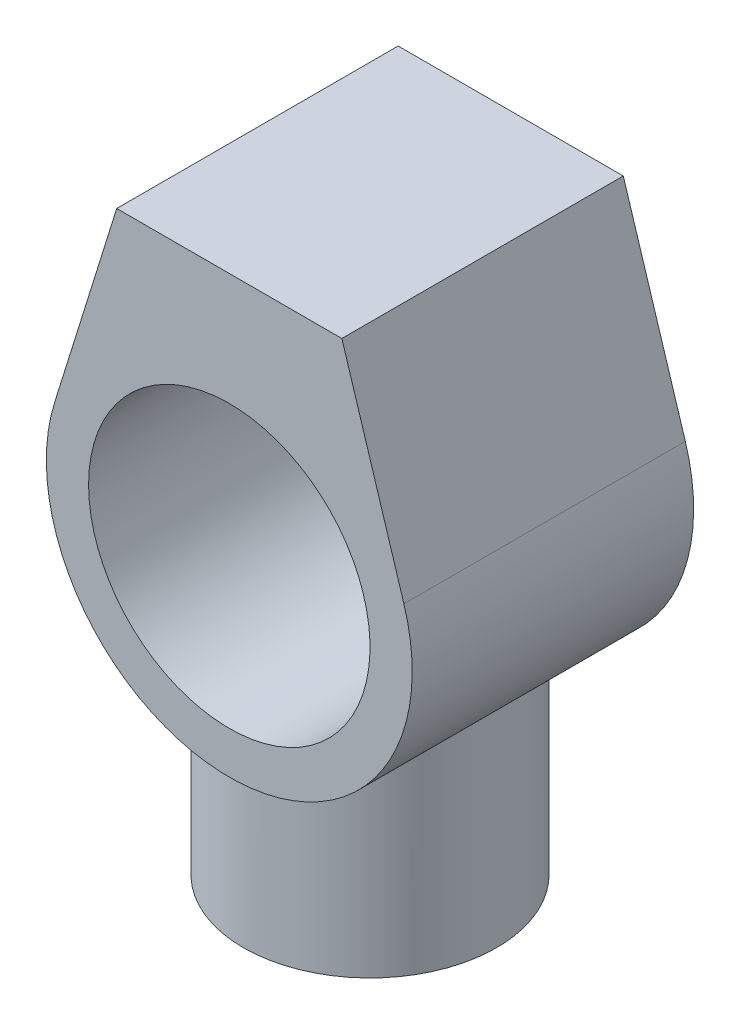
SolidWorks part; units mm, degrees
material "普通碳钢"
ref_plane "Front Plane" through (0, 0, 0) normal (0, 0, 1) x (1, 0, 0)
ref_plane "Top Plane" through (0, 0, 0) normal (0, 1, 0) x (1, 0, 0)
ref_plane "Right Plane" through (0, 0, 0) normal (1, 0, 0) x (0, 0, -1)
sketch "Sketch1" plane through (0, 0, 0) normal (0, 0, 1) x (1, 0, 0)
  line L0 (-40, 90) -> (40, 90)
  line L1 (-40, 90) -> (-62.0475, 19.3678)
  line L2 (40, 90) -> (62.0475, 19.3678)
  circle A0 centre (0, 0) radius 50
  arc A1 (-62.0475, 19.3678) -> (62.0475, 19.3678) centre (0, 0) ccw
  point P7 (0, 90)
  dimension "D1" = 100
  dimension "D2" = 65
  dimension "D3" = 80
  dimension "D4" = 90
extrude "Boss-Extrude1" add sketch "Sketch1" along normal mid plane 100
ref_plane "Plane1" through (0, -120, 0) normal (0, 1, 0) x (1, 0, 0)
sketch "Sketch2" plane through (0, -120, 0) normal (0, 1, 0) x (1, 0, 0)
  line L0 (0, 45) -> (0, -45) construction
  line L1 (-45, 0) -> (45, 0) construction
  circle A0 centre (0, 0) radius 45
  circle A1 centre (0, 0) radius 37 construction
  circle A2 centre (0, 37) radius 5
  circle A3 centre (0, 0) radius 37 construction
  circle A4 centre (32.0429, 18.5) radius 5
  circle A5 centre (0, 0) radius 37 construction
  circle A6 centre (32.0429, -18.5) radius 5
  circle A7 centre (0, 0) radius 37 construction
  circle A8 centre (0, -37) radius 5
  circle A9 centre (0, 0) radius 37 construction
  circle A10 centre (-32.0429, -18.5) radius 5
  circle A11 centre (0, 0) radius 37 construction
  circle A12 centre (-32.0429, 18.5) radius 5
  point P27 (0, 0)
  dimension "D1" = 90
  dimension "D2" = 74
  dimension "D3" = 10
  dimension "D4" = 6
extrude "Boss-Extrude2" add sketch "Sketch2" along normal up to surface (55 mm away)
scale "缩放比例1" scale about centroid uniform scaling yes scale factor 0.135065
